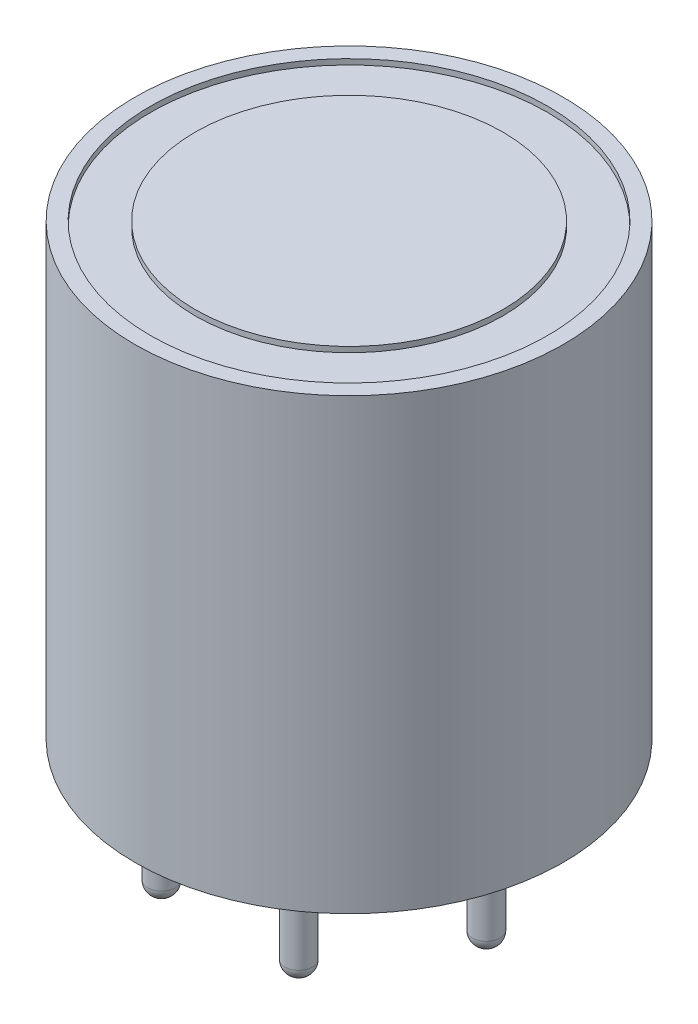
SolidWorks part; units mm, degrees
ref_plane "Front Plane" through (0, 0, 0) normal (0, 0, 1) x (1, 0, 0)
ref_plane "Top Plane" through (0, 0, 0) normal (0, 1, 0) x (1, 0, 0)
ref_plane "Right Plane" through (0, 0, 0) normal (1, 0, 0) x (0, 0, -1)
sketch "Sketch1" plane through (0, 0, 0) normal (0, 1, 0) x (1, 0, 0)
  circle A0 centre (0, 0) radius 11.7
  dimension "D1" = 23.4
extrude "Boss-Extrude1" add sketch "Sketch1" along normal blind 24.5
sketch "Sketch2" plane through (0, 24.5, 0) normal (0, 1, 0) x (1, 0, 0)
  circle A0 centre (0, 0) radius 10.85
  dimension "D1" = 21.7
extrude "Cut-Extrude1" cut sketch "Sketch2" against normal blind 0.3
sketch "Sketch3" plane through (0, 24.2, 0) normal (0, 1, 0) x (1, 0, 0)
  circle A0 centre (0, 0) radius 8.4
extrude "Boss-Extrude2" add sketch "Sketch3" along normal blind 0.3
sketch "Sketch6" plane through (0, 0, 0) normal (0, -1, 0) x (1, 0, 0)
  line L0 (11.7, 0) -> (-11.7, 0) construction
  line L1 (0, 11.7) -> (0, -11.7) construction
  line L2 (0, 0) -> (5.85, 10.1325) construction
  line L3 (0, 0) -> (-3.75, 6.4952) construction
  line L4 (-3.75, 6.4952) -> (-5.85, 10.1325) construction
  circle A0 centre (0, 0) radius 7.5 construction
  circle A1 centre (0, 0) radius 11.7 construction
  circle A2 centre (7.5, 0) radius 0.75
  circle A3 centre (3.75, 6.4952) radius 0.75
  circle A4 centre (-3.75, 6.4952) radius 0.75
  circle A5 centre (3.75, -6.4952) radius 0.75
  circle A6 centre (-3.75, -6.4952) radius 0.75
  dimension "D1" = 15
  dimension "D2" = 1.5
  dimension "D3" = 60
  dimension "D6" = 60
  dimension "D4" = 3
  dimension "D5" = 3
extrude "Boss-Extrude3" add sketch "Sketch6" along normal blind 6
fillet "Fillet12" radius 0.7 5 edges at (-3.75, -6, 5.7452) (-3.75, -6, -7.2452) (3.75, -6, -7.2452) (3.75, -6, 5.7452) (7.5, -6, -0.75)
